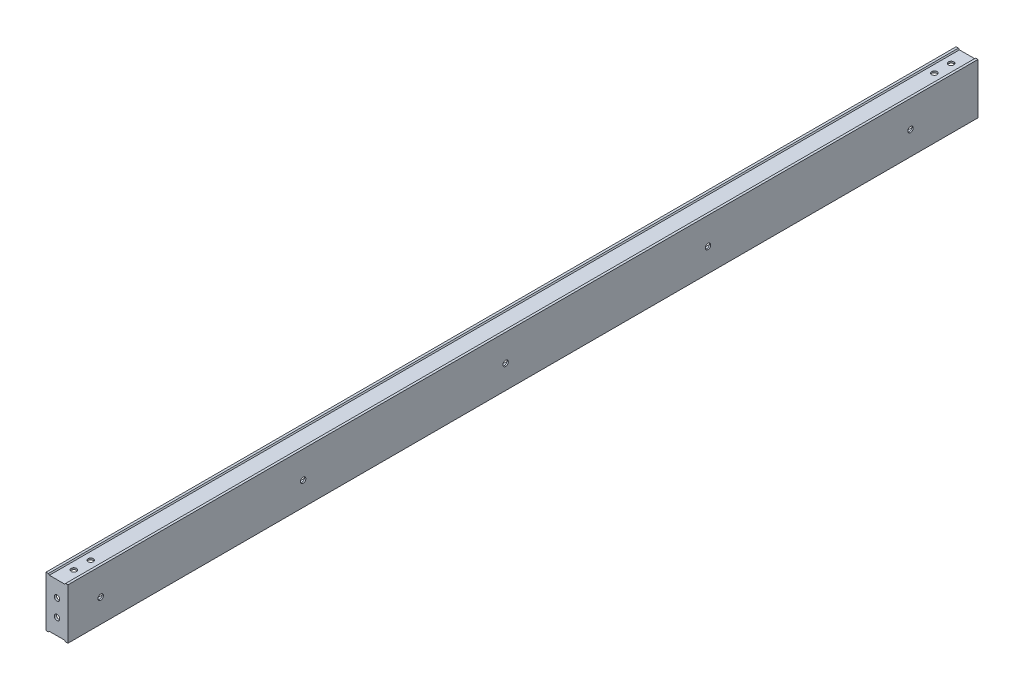
SolidWorks part; units mm, degrees
material "6061-T6 (SS)"
ref_plane "前视基准面" through (0, 0, 0) normal (0, 0, 1) x (1, 0, 0)
ref_plane "上视基准面" through (0, 0, 0) normal (0, 1, 0) x (1, 0, 0)
ref_plane "右视基准面" through (0, 0, 0) normal (1, 0, 0) x (0, 0, -1)
sketch "Model" plane through (0, 0, 0) normal (0, 0, 1) x (1, 0, 0)
  line L0 (11746.24, -58203.4132) -> (11636.4348, -58203.4132) construction
  line L1 (11739.24, -58278.4132) -> (11736.24, -58275.4132)
  line L11 (11746.24, -58128.4132) -> (11746.24, -58278.4132)
  line L12 (11739.24, -58128.4132) -> (11746.24, -58128.4132)
  line L13 (11739.24, -58128.4132) -> (11736.24, -58131.4132)
  line L14 (11691.24, -58131.4132) -> (11736.24, -58131.4132)
  line L15 (11688.24, -58128.4132) -> (11691.24, -58131.4132)
  line L16 (11688.24, -58128.4132) -> (11681.24, -58128.4132)
  line L17 (11681.24, -58128.4132) -> (11681.24, -58136.4132)
  line L18 (11681.24, -58136.4132) -> (11739.24, -58136.4132)
  line L19 (11742.24, -58139.4132) -> (11742.24, -58267.4132)
  line L20 (11739.24, -58278.4132) -> (11746.24, -58278.4132)
  line L23 (11681.24, -58270.4132) -> (11739.24, -58270.4132)
  line L24 (11681.24, -58278.4132) -> (11681.24, -58270.4132)
  line L25 (11688.24, -58278.4132) -> (11681.24, -58278.4132)
  line L26 (11688.24, -58278.4132) -> (11691.24, -58275.4132)
  line L27 (11691.24, -58275.4132) -> (11736.24, -58275.4132)
  arc A2 (11742.24, -58139.4132) -> (11739.24, -58136.4132) centre (11739.24, -58139.4132) ccw
  arc A3 (11742.24, -58267.4132) -> (11739.24, -58270.4132) centre (11739.24, -58267.4132) cw
  point P12 (11742.24, -58203.4132)
  point P16 (11742.74, -58278.4132)
  dimension "D8" = 3
  dimension "D1" = 150
  dimension "D2" = 4
  dimension "D3" = 65
  dimension "D4" = 8
  dimension "D5" = 7
  dimension "D6" = 10
  dimension "D7" = 5
extrude "凸台-拉伸1" add sketch "Model" along normal blind 2697 contours L11 L20 L1 L27 L26 L25 L24 L23 A3 L19 A2 L18 L17 L16 L15 L14 L13 L12
sketch "草图2" plane through (0, 0, 2697) normal (0, 0, 1) x (1, 0, 0)
  line L0 (11681.24, -58270.4132) -> (11739.24, -58270.4132) construction
  line L1 (11681.24, -58136.4132) -> (11742.24, -58136.4132)
  line L2 (11681.24, -58136.4132) -> (11681.24, -58270.4132)
  line L3 (11681.24, -58270.4132) -> (11742.24, -58270.4132)
  line L4 (11742.24, -58136.4132) -> (11742.24, -58270.4132)
  line L5 (11742.24, -58139.4132) -> (11742.24, -58267.4132) construction
extrude "凸台-拉伸2" add sketch "草图2" against normal blind 6
sketch "草图3" plane through (0, 0, 0) normal (0, 0, -1) x (-1, 0, 0)
  line L0 (-11681.24, -58270.4132) -> (-11739.24, -58270.4132) construction
  line L1 (-11681.24, -58136.4132) -> (-11742.24, -58136.4132)
  line L2 (-11681.24, -58136.4132) -> (-11681.24, -58270.4132)
  line L3 (-11681.24, -58270.4132) -> (-11742.24, -58270.4132)
  line L4 (-11742.24, -58136.4132) -> (-11742.24, -58270.4132)
  line L5 (-11742.24, -58139.4132) -> (-11742.24, -58267.4132) construction
extrude "凸台-拉伸3" add sketch "草图3" against normal blind 6
hole_wizard "Ø16.0 (16) 直径孔1" positions "草图4" profile "草图5" hole size "Ø16.0" standard "GB"
sketch "草图4" plane through (11742.24, 0, 0) normal (-1, 0, 0) x (0, 0, 1)
  line L0 (1400, -58208.4132) -> (2000, -58208.4132)
  line L2 (2697, -58128.4132) -> (0, -58128.4132) construction
  line L3 (0, -58128.4132) -> (0, -58278.4132) construction
  point P0 (200, -58208.4132)
  point P2 (800, -58208.4132)
  point P4 (1400, -58208.4132)
  point P6 (2000, -58208.4132)
  point P28 (2600, -58208.4132)
  dimension "D1" = 600
  dimension "D2" = 80
  dimension "D3" = 200
  dimension "D4" = 600
  dimension "D5" = 600
  dimension "D6" = 600
sketch "草图5" plane through (11742.24, -58208.4132, 200) normal (0, 1, 0) x (0, 0, 1)
  line L0 (0, 0) -> (0, 9.8069)
  line L1 (0, 9.8069) -> (8, 5)
  line L2 (8, 5) -> (8, 0)
  line L5 (8, 0) -> (0, 0)
  line L10 (0, 9.8069) -> (-8, 5) construction
  line L11 (0, -6.35) -> (0, 107.95) construction
  dimension "孔直径" = 16
  dimension "孔深度" = 5
  dimension "导头角度" = 118
hole_wizard "Ø16.0 (16) 直径孔2" positions "草图6" profile "草图8" hole size "Ø16.0" standard "GB" end condition through all
sketch "草图6" plane through (0, -58275.4132, 0) normal (0, -1, 0) x (-1, 0, 0)
  line L0 (-11681.24, -2697) -> (-11681.24, 0) construction
  line L1 (-11691.24, -2697) -> (-11736.24, -2697) construction
  point P0 (-11713.74, -2647)
  dimension "D1" = 32.5
  dimension "D2" = 50
sketch "草图8" plane through (11713.74, -58275.4132, 2647) normal (1, 0, 0) x (0, 0, -1)
  line L0 (0, 0) -> (0, 147)
  line L1 (0, 147) -> (8, 147)
  line L2 (8, 147) -> (8, 0)
  line L5 (8, 0) -> (0, 0)
  line L11 (0, -6.35) -> (0, 107.95) construction
  dimension "通孔孔直径" = 16
  dimension "通孔孔深度" = 147
pattern_linear "阵列(线性)1" count 2 spacing 50 along (0, 0, -1) of "Ø16.0 (16) 直径孔2"
hole_wizard "Ø16.0 (16) 直径孔3" positions "草图9" profile "草图10" hole size "Ø16.0" standard "GB" end condition through all
sketch "草图9" plane through (0, -58275.4132, 0) normal (0, -1, 0) x (-1, 0, 0)
  line L0 (-11691.24, 0) -> (-11736.24, 0) construction
  line L1 (-11746.24, -2697) -> (-11746.24, 0) construction
  line L2 (-11713.74, -47) -> (-11713.74, -135.4838) construction
  point P0 (-11713.74, -47)
  point P2 (-11713.74, -97)
  dimension "D1" = 47
  dimension "D2" = 50
  dimension "D3" = 32.5
sketch "草图10" plane through (11713.74, -58275.4132, 47) normal (1, 0, 0) x (0, 0, -1)
  line L0 (0, 0) -> (0, 147)
  line L1 (0, 147) -> (8, 147)
  line L2 (8, 147) -> (8, 0)
  line L5 (8, 0) -> (0, 0)
  line L11 (0, -6.35) -> (0, 107.95) construction
  dimension "通孔孔直径" = 16
  dimension "通孔孔深度" = 147
hole_wizard "Ø16.0 (16) 直径孔4" positions "草图11" profile "草图12" hole size "Ø16.0" standard "GB" end condition through all
sketch "草图11" plane through (0, 0, 2697) normal (0, 0, 1) x (1, 0, 0)
  line L0 (11681.24, -58278.4132) -> (11681.24, -58128.4132) construction
  line L1 (11688.24, -58128.4132) -> (11681.24, -58128.4132) construction
  point P0 (11713.74, -58178.4132)
  dimension "D1" = 32.5
  dimension "D2" = 50
sketch "草图12" plane through (11713.74, -58178.4132, 2697) normal (1, 0, 0) x (0, -1, 0)
  line L0 (0, 0) -> (0, 2697)
  line L1 (0, 2697) -> (8, 2697)
  line L2 (8, 2697) -> (8, 0)
  line L5 (8, 0) -> (0, 0)
  line L11 (0, -6.35) -> (0, 107.95) construction
  dimension "通孔孔直径" = 16
  dimension "通孔孔深度" = 2697
pattern_linear "阵列(线性)2" count 2 spacing 50 along (0, -1, 0) of "Ø16.0 (16) 直径孔4"
